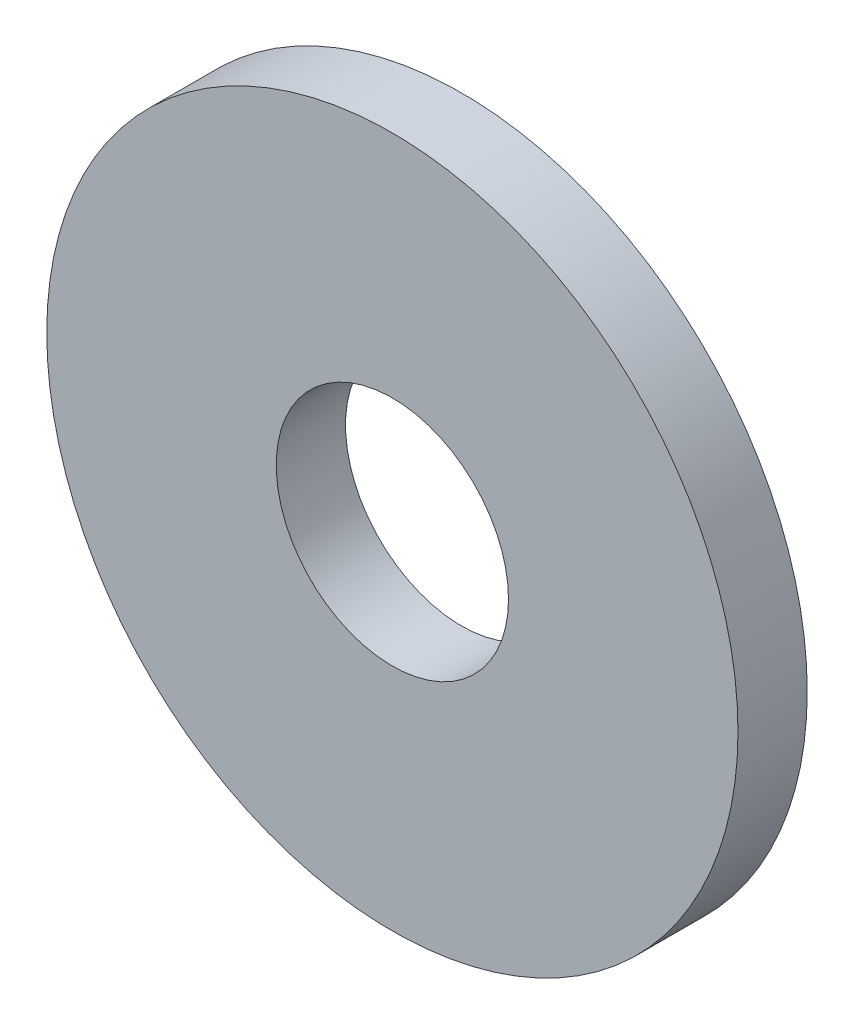
SolidWorks part; units mm, degrees
ref_plane "前视基准面" through (0, 0, 0) normal (0, 0, 1) x (1, 0, 0)
ref_plane "上视基准面" through (0, 0, 0) normal (0, 1, 0) x (1, 0, 0)
ref_plane "右视基准面" through (0, 0, 0) normal (1, 0, 0) x (0, 0, -1)
sketch "草图1" plane through (0, 0, 0) normal (0, 0, 1) x (1, 0, 0)
  circle A0 centre (0, 0) radius 14.97
  circle A1 centre (0, 0) radius 5.03
  dimension "D1" = 29.94
  dimension "D2" = 10.06
extrude "凸台-拉伸1" add sketch "草图1" along normal blind 3 contours A0
